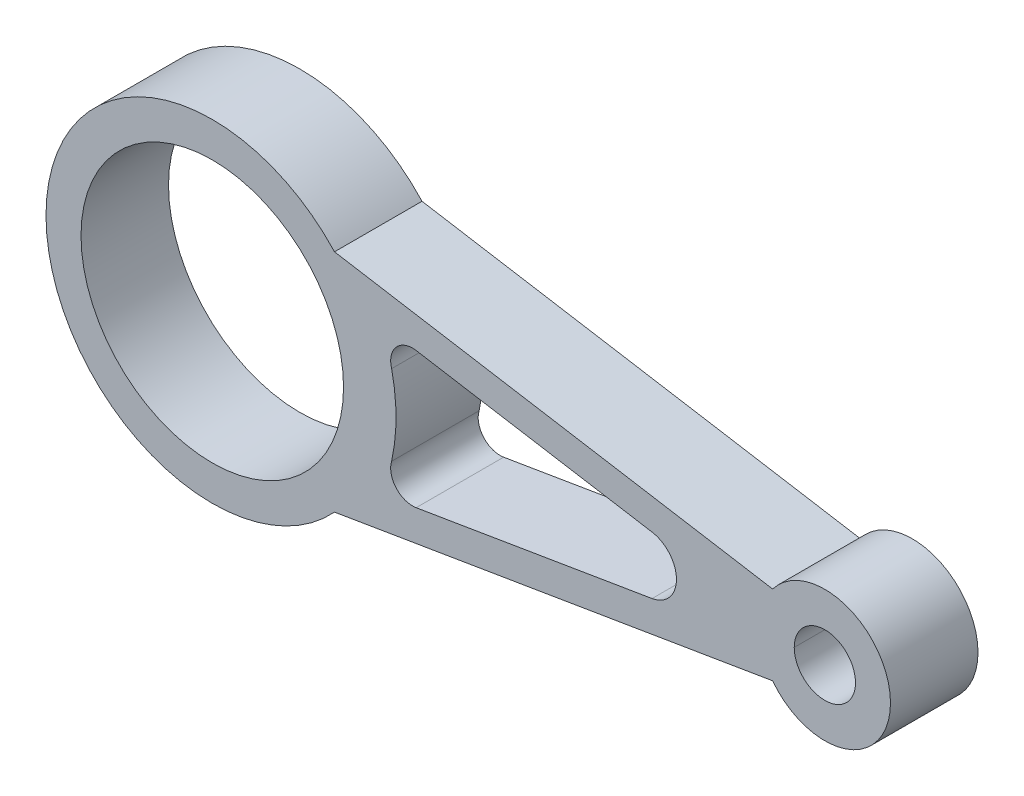
SolidWorks part; units mm, degrees
material "Plain Carbon Steel"
ref_plane "Front Plane" through (0, 0, 0) normal (0, 0, 1) x (1, 0, 0)
ref_plane "Top Plane" through (0, 0, 0) normal (0, 1, 0) x (1, 0, 0)
ref_plane "Right Plane" through (0, 0, 0) normal (1, 0, 0) x (0, 0, -1)
sketch "Sketch1" plane through (0, 0, 0) normal (0, 0, 1) x (1, 0, 0)
  line L0 (-114.0385, 0) -> (233.8108, 0) construction
  line L1 (27.9355, -25.7606) -> (128.0638, -9.0844)
  line L2 (27.9355, 25.7606) -> (128.0638, 9.0844)
  circle A0 centre (0, 0) radius 30
  arc A1 (27.9355, 25.7606) -> (27.9355, -25.7606) centre (0, 0) ccw
  arc A3 (128.0638, -9.0844) -> (128.0638, 9.0844) centre (140, 0) ccw
  circle A4 centre (140, 0) radius 7
  dimension "D1" = 60
  dimension "D2" = 14
  dimension "D3" = 140
  dimension "D4" = 30
  dimension "D5" = 76
extrude "Boss-Extrude1" add sketch "Sketch1" along normal mid plane 20
sketch "Sketch2" plane through (0, 0, 10) normal (0, 0, 1) x (1, 0, 0)
  line L0 (-61.1243, 0) -> (180.897, 0) construction
  line L1 (46.5914, 15.5571) -> (100.5143, 6.5763)
  line L2 (46.5914, -15.5571) -> (100.5143, -6.5763)
  line L3 (128.0638, 9.0844) -> (27.9355, 25.7606) construction
  line L4 (27.9355, -25.7606) -> (128.0638, -9.0844) construction
  arc A0 (46.5914, 15.5571) -> (40.9876, 9.1659) centre (45.77, 10.625) ccw
  arc A1 (40.9876, -9.1659) -> (40.9876, 9.1659) centre (0, 0) ccw
  arc A3 (46.5914, -15.5571) -> (40.9876, -9.1659) centre (45.77, -10.625) cw
  arc A4 (100.5143, 6.5763) -> (100.5143, -6.5763) centre (99.419, 0) cw
  circle A6 centre (0, 0) radius 30 construction
  dimension "D1" = 5
  dimension "D2" = 8.5
  dimension "D3" = 7
  dimension "D4" = 6.6669
  dimension "D6" = 12
extrude "Cut-Extrude1" cut sketch "Sketch2" against normal through all
split line "Split Line1"
